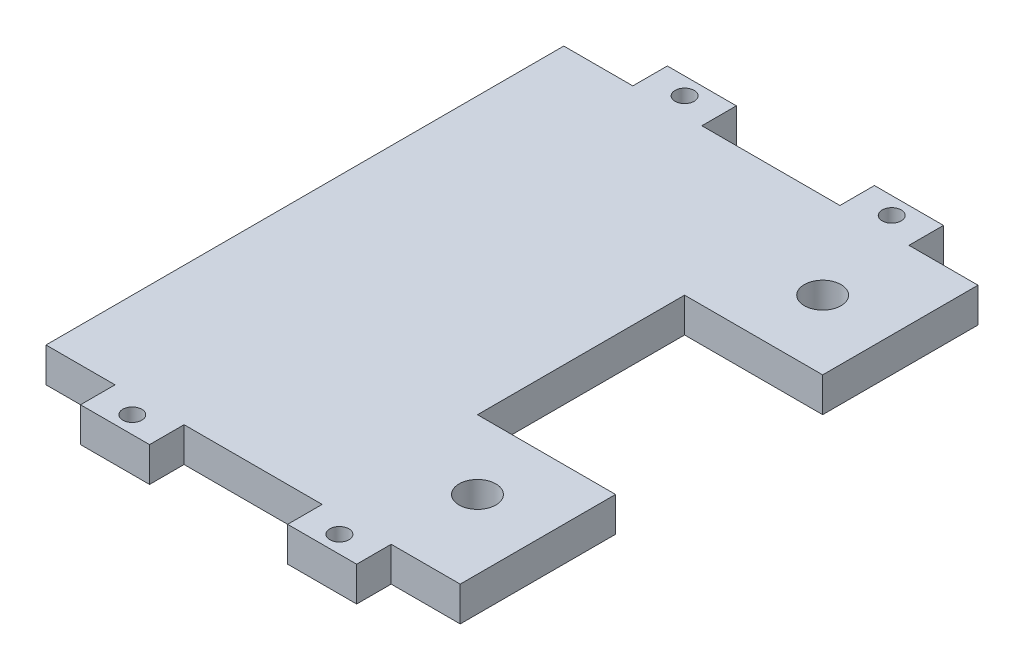
SolidWorks part; units mm, degrees
material "Beech"
ref_plane "Front Plane" through (0, 0, 0) normal (0, 0, 1) x (1, 0, 0)
ref_plane "Top Plane" through (0, 0, 0) normal (0, 1, 0) x (1, 0, 0)
ref_plane "Right Plane" through (0, 0, 0) normal (1, 0, 0) x (0, 0, -1)
sketch "Sketch1" plane through (0, 0, 0) normal (0, 1, 0) x (1, 0, 0)
  line L0 (-38.1, 53.975) -> (-38.1, -53.975)
  line L1 (-38.1, 53.975) -> (38.1, 53.975)
  line L2 (-38.1, -53.975) -> (38.1, -53.975)
  line L3 (38.1, 53.975) -> (38.1, -53.975)
  line L4 (-38.1, 53.975) -> (38.1, -53.975) construction
  line L5 (-38.1, -53.975) -> (38.1, 53.975) construction
  point P1 (0, 0)
  dimension "D1" = 107.95
  dimension "D2" = 76.2
extrude "Boss-Extrude1" add sketch "Sketch1" along normal blind 6.35
sketch "Sketch2" plane through (0, 6.35, 0) normal (0, 1, 0) x (1, 0, 0)
  line L0 (38.1, 53.975) -> (-38.1, 53.975) construction
  line L1 (-38.1, 53.975) -> (-25.4, 53.975)
  line L2 (-38.1, 53.975) -> (-38.1, 47.625)
  line L3 (-38.1, 47.625) -> (-25.4, 47.625)
  line L4 (-25.4, 53.975) -> (-25.4, 47.625)
  line L5 (-12.7, 53.975) -> (12.7, 53.975)
  line L6 (-12.7, 53.975) -> (-12.7, 47.625)
  line L7 (-12.7, 47.625) -> (12.7, 47.625)
  line L8 (12.7, 53.975) -> (12.7, 47.625)
  line L9 (0, 0) -> (28.6019, 0) construction
  line L10 (38.1, 53.975) -> (25.4, 53.975)
  line L11 (38.1, 53.975) -> (38.1, 47.625)
  line L12 (38.1, 47.625) -> (25.4, 47.625)
  line L13 (25.4, 53.975) -> (25.4, 47.625)
  line L14 (25.4, -53.975) -> (25.4, -47.625)
  line L15 (38.1, -47.625) -> (25.4, -47.625)
  line L16 (38.1, -53.975) -> (38.1, -47.625)
  line L17 (38.1, -53.975) -> (25.4, -53.975)
  line L18 (12.7, -53.975) -> (12.7, -47.625)
  line L19 (-12.7, -47.625) -> (12.7, -47.625)
  line L20 (-12.7, -53.975) -> (-12.7, -47.625)
  line L21 (-12.7, -53.975) -> (12.7, -53.975)
  line L22 (-25.4, -53.975) -> (-25.4, -47.625)
  line L23 (-38.1, -47.625) -> (-25.4, -47.625)
  line L24 (-38.1, -53.975) -> (-38.1, -47.625)
  line L25 (-38.1, -53.975) -> (-25.4, -53.975)
  line L26 (-38.1, 47.625) -> (38.1, 47.625) construction
  line L27 (-25.4, 50.8) -> (-12.7, 50.8) construction
  line L28 (12.7, 50.8) -> (25.4, 50.8) construction
  circle A0 centre (-19.05, 50.8) radius 1.7526
  circle A1 centre (19.05, 50.8) radius 1.7526
  circle A2 centre (19.05, -50.8) radius 1.7526
  circle A3 centre (-19.05, -50.8) radius 1.7526
  dimension "D5" = 3.5052
  dimension "D1" = 6.35
  dimension "D2" = 12.7
  dimension "D3" = 12.7
  dimension "D4" = 25.4
  dimension "D6" = 12.7
extrude "Cut-Extrude1" cut sketch "Sketch2" against normal blind 6.35
sketch "Sketch3" plane through (0, 6.35, 0) normal (0, 1, 0) x (1, 0, 0)
  line L0 (38.1, -47.625) -> (38.1, 47.625) construction
  line L1 (38.1, 19.05) -> (12.7, 19.05)
  line L2 (38.1, 19.05) -> (38.1, -19.05)
  line L3 (38.1, -19.05) -> (12.7, -19.05)
  line L4 (12.7, 19.05) -> (12.7, -19.05)
  line L5 (-38.1, 0) -> (38.1, 0) construction
  line L6 (-38.1, 47.625) -> (-38.1, -47.625) construction
  line L7 (38.1, 19.05) -> (12.7, -19.05) construction
  line L8 (12.7, 19.05) -> (38.1, -19.05) construction
  point P11 (25.4, 0)
  dimension "D1" = 25.4
  dimension "D2" = 38.1
extrude "Cut-Extrude2" cut sketch "Sketch3" against normal up to next
ref_plane "Plane1" through (0, 0, -50.8) normal (0, 0, -1) x (-1, 0, 0)
ref_plane "Plane2" through (0, 0, 50.8) normal (0, 0, 1) x (1, 0, 0)
hole_wizard "#6 Clearance Hole1" positions "Sketch7" profile "Sketch6" hole size "#6" standard "ANSI Inch"
sketch "Sketch7" plane through (0, 6.35, 0) normal (0, 1, 0) x (1, 0, 0)
  point P0 (-19.05, 50.8)
  point P3 (19.05, 50.8)
  point P6 (-19.05, -50.8)
  point P9 (19.05, -50.8)
sketch "Sketch6" plane through (-19.05, 6.35, -50.8) normal (1, 0, 0) x (0, 0, 1)
  line L0 (0, 0) -> (0, 7.4031)
  line L1 (0, 7.4031) -> (1.7526, 6.35)
  line L2 (1.7526, 6.35) -> (1.7526, 0)
  line L5 (1.7526, 0) -> (0, 0)
  line L10 (0, 7.4031) -> (-1.7526, 6.35) construction
  line L11 (0, -6.35) -> (0, 107.95) construction
  dimension "Hole Dia." = 3.5052
  dimension "Hole Depth" = 6.35
  dimension "Drill Angle" = 118
hole_wizard "1/4 Clearance Hole1" positions "Sketch8" profile "Sketch9" hole size "1/4" standard "ANSI Inch" end condition up to next
sketch "Sketch8" plane through (0, 0, 0) normal (0, -1, 0) x (-1, 0, 0)
  line L0 (-38.1, 19.05) -> (-38.1, 47.625) construction
  line L1 (-38.1, 19.05) -> (-12.7, 19.05) construction
  line L2 (0, 0) -> (-12.7, 0) construction
  line L3 (-12.7, 19.05) -> (-12.7, -19.05) construction
  point P0 (-25.4, 31.75)
  point P88 (-25.4, -31.75)
  dimension "D1" = 12.7
  dimension "D2" = 12.7
sketch "Sketch9" plane through (25.4, 0, -31.75) normal (1, 0, 0) x (0, 0, -1)
  line L0 (0, 0) -> (0, 6.35)
  line L1 (0, 6.35) -> (3.3782, 6.35)
  line L2 (3.3782, 6.35) -> (3.3782, 0)
  line L5 (3.3782, 0) -> (0, 0)
  line L11 (0, -6.35) -> (0, 107.95) construction
  dimension "Thru Hole Dia." = 6.7564
  dimension "Thru Hole Depth" = 6.35
